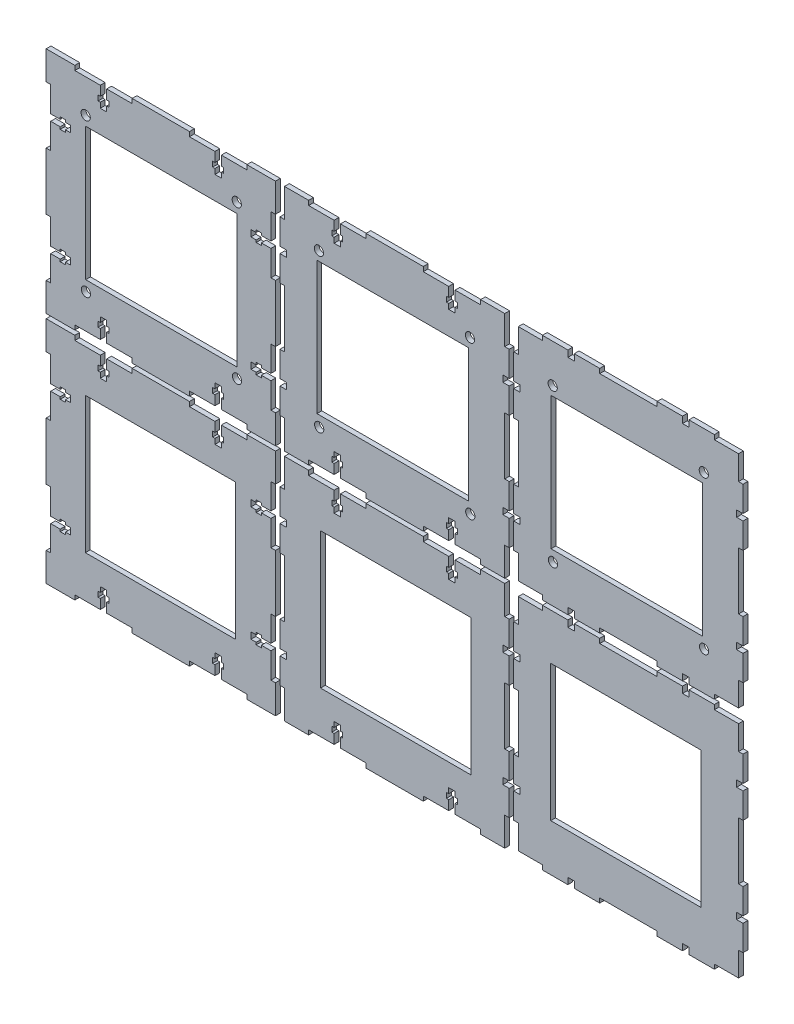
SolidWorks part; units mm, degrees
ref_plane "Front Plane" through (0, 0, 0) normal (0, 0, 1) x (1, 0, 0)
ref_plane "Top Plane" through (0, 0, 0) normal (0, 1, 0) x (1, 0, 0)
ref_plane "Right Plane" through (0, 0, 0) normal (1, 0, 0) x (0, 0, -1)
sketch "Model" plane through (0, 0, 0) normal (0, 0, 1) x (1, 0, 0)
  line L0 (0, 154.3975) -> (0, 135.4704)
  line L1 (0, 135.4704) -> (2.9806, 135.4704)
  line L2 (2.9806, 135.4704) -> (2.9806, 118.6546)
  line L3 (2.9806, 118.6546) -> (9.2897, 118.6546)
  line L4 (9.2897, 118.6546) -> (9.2897, 120.1449)
  line L5 (9.2897, 120.1449) -> (12.7174, 120.1449)
  line L6 (12.7174, 120.1449) -> (12.7174, 118.6546)
  line L7 (12.7174, 118.6546) -> (16.1452, 118.6546)
  line L8 (16.1452, 118.6546) -> (16.1452, 114.432)
  line L9 (16.1452, 114.432) -> (12.7174, 114.432)
  line L10 (12.7174, 114.432) -> (12.7174, 112.9417)
  line L11 (12.7174, 112.9417) -> (9.2897, 112.9417)
  line L12 (9.2897, 112.9417) -> (9.2897, 114.432)
  line L13 (9.2897, 114.432) -> (2.9806, 114.432)
  line L14 (2.9806, 114.432) -> (2.9806, 97.6162)
  line L15 (2.9806, 97.6162) -> (0, 97.6162)
  line L16 (0, 97.6162) -> (0, 59.762)
  line L17 (0, 59.762) -> (2.9806, 59.762)
  line L18 (2.9806, 59.762) -> (2.9806, 42.9462)
  line L19 (2.9806, 42.9462) -> (9.2897, 42.9462)
  line L20 (9.2897, 42.9462) -> (9.2897, 44.4365)
  line L21 (9.2897, 44.4365) -> (12.7174, 44.4365)
  line L22 (12.7174, 44.4365) -> (12.7174, 42.9462)
  line L23 (12.7174, 42.9462) -> (16.1452, 42.9462)
  line L24 (16.1452, 42.9462) -> (16.1452, 38.7236)
  line L25 (16.1452, 38.7236) -> (12.7174, 38.7236)
  line L26 (12.7174, 38.7236) -> (12.7174, 37.2332)
  line L27 (12.7174, 37.2332) -> (9.2897, 37.2332)
  line L28 (9.2897, 37.2332) -> (9.2897, 38.7236)
  line L29 (9.2897, 38.7236) -> (2.9806, 38.7236)
  line L30 (2.9806, 38.7236) -> (2.9806, 21.9078)
  line L31 (2.9806, 21.9078) -> (0, 21.9078)
  line L32 (0, 21.9078) -> (0, 2.9806)
  line L33 (0, 2.9806) -> (18.9271, 2.9806)
  line L34 (18.9271, 2.9806) -> (18.9271, 5.9613)
  line L35 (18.9271, 5.9613) -> (35.7429, 5.9613)
  line L36 (35.7429, 5.9613) -> (35.7429, 12.2703)
  line L37 (35.7429, 12.2703) -> (34.2526, 12.2703)
  line L38 (34.2526, 12.2703) -> (34.2526, 15.6981)
  line L39 (34.2526, 15.6981) -> (35.7429, 15.6981)
  line L40 (35.7429, 15.6981) -> (35.7429, 19.1258)
  line L41 (35.7429, 19.1258) -> (39.9655, 19.1258)
  line L42 (39.9655, 19.1258) -> (39.9655, 15.6981)
  line L43 (39.9655, 15.6981) -> (41.4558, 15.6981)
  line L44 (41.4558, 15.6981) -> (41.4558, 12.2703)
  line L45 (41.4558, 12.2703) -> (39.9655, 12.2703)
  line L46 (39.9655, 12.2703) -> (39.9655, 5.9613)
  line L47 (39.9655, 5.9613) -> (56.7813, 5.9613)
  line L48 (56.7813, 5.9613) -> (56.7813, 2.9806)
  line L49 (56.7813, 2.9806) -> (94.6355, 2.9806)
  line L50 (94.6355, 2.9806) -> (94.6355, 5.9613)
  line L51 (94.6355, 5.9613) -> (111.4513, 5.9613)
  line L52 (111.4513, 5.9613) -> (111.4513, 12.2703)
  line L53 (111.4513, 12.2703) -> (109.961, 12.2703)
  line L54 (109.961, 12.2703) -> (109.961, 15.6981)
  line L55 (109.961, 15.6981) -> (111.4513, 15.6981)
  line L56 (111.4513, 15.6981) -> (111.4513, 19.1258)
  line L57 (111.4513, 19.1258) -> (115.6739, 19.1258)
  line L58 (115.6739, 19.1258) -> (115.6739, 15.6981)
  line L59 (115.6739, 15.6981) -> (117.1643, 15.6981)
  line L60 (117.1643, 15.6981) -> (117.1643, 12.2703)
  line L61 (117.1643, 12.2703) -> (115.6739, 12.2703)
  line L62 (115.6739, 12.2703) -> (115.6739, 5.9613)
  line L63 (115.6739, 5.9613) -> (132.4897, 5.9613)
  line L64 (132.4897, 5.9613) -> (132.4897, 2.9806)
  line L65 (132.4897, 2.9806) -> (151.4169, 2.9806)
  line L66 (151.4169, 2.9806) -> (151.4169, 21.9078)
  line L67 (151.4169, 21.9078) -> (148.4362, 21.9078)
  line L68 (148.4362, 21.9078) -> (148.4362, 38.7236)
  line L69 (148.4362, 38.7236) -> (142.1272, 38.7236)
  line L70 (142.1272, 38.7236) -> (142.1272, 37.2332)
  line L71 (142.1272, 37.2332) -> (138.6994, 37.2332)
  line L72 (138.6994, 37.2332) -> (138.6994, 38.7236)
  line L73 (138.6994, 38.7236) -> (135.2717, 38.7236)
  line L74 (135.2717, 38.7236) -> (135.2717, 42.9462)
  line L75 (135.2717, 42.9462) -> (138.6994, 42.9462)
  line L76 (138.6994, 42.9462) -> (138.6994, 44.4365)
  line L77 (138.6994, 44.4365) -> (142.1272, 44.4365)
  line L78 (142.1272, 44.4365) -> (142.1272, 42.9462)
  line L79 (142.1272, 42.9462) -> (148.4362, 42.9462)
  line L80 (148.4362, 42.9462) -> (148.4362, 59.762)
  line L81 (148.4362, 59.762) -> (151.4169, 59.762)
  line L82 (151.4169, 59.762) -> (151.4169, 97.6162)
  line L83 (151.4169, 97.6162) -> (148.4362, 97.6162)
  line L84 (148.4362, 97.6162) -> (148.4362, 114.432)
  line L85 (148.4362, 114.432) -> (142.1272, 114.432)
  line L86 (142.1272, 114.432) -> (142.1272, 112.9417)
  line L87 (142.1272, 112.9417) -> (138.6994, 112.9417)
  line L88 (138.6994, 112.9417) -> (138.6994, 114.432)
  line L89 (138.6994, 114.432) -> (135.2717, 114.432)
  line L90 (135.2717, 114.432) -> (135.2717, 118.6546)
  line L91 (135.2717, 118.6546) -> (138.6994, 118.6546)
  line L92 (138.6994, 118.6546) -> (138.6994, 120.1449)
  line L93 (138.6994, 120.1449) -> (142.1272, 120.1449)
  line L94 (142.1272, 120.1449) -> (142.1272, 118.6546)
  line L95 (142.1272, 118.6546) -> (148.4362, 118.6546)
  line L96 (148.4362, 118.6546) -> (148.4362, 135.4704)
  line L97 (148.4362, 135.4704) -> (151.4169, 135.4704)
  line L98 (151.4169, 135.4704) -> (151.4169, 154.3975)
  line L99 (151.4169, 154.3975) -> (132.4897, 154.3975)
  line L100 (132.4897, 154.3975) -> (132.4897, 151.4169)
  line L101 (132.4897, 151.4169) -> (115.6739, 151.4169)
  line L102 (115.6739, 151.4169) -> (115.6739, 145.1078)
  line L103 (115.6739, 145.1078) -> (117.1643, 145.1078)
  line L104 (117.1643, 145.1078) -> (117.1643, 141.6801)
  line L105 (117.1643, 141.6801) -> (115.6739, 141.6801)
  line L106 (115.6739, 141.6801) -> (115.6739, 138.2523)
  line L107 (115.6739, 138.2523) -> (111.4513, 138.2523)
  line L108 (111.4513, 138.2523) -> (111.4513, 141.6801)
  line L109 (111.4513, 141.6801) -> (109.961, 141.6801)
  line L110 (109.961, 141.6801) -> (109.961, 145.1078)
  line L111 (109.961, 145.1078) -> (111.4513, 145.1078)
  line L112 (111.4513, 145.1078) -> (111.4513, 151.4169)
  line L113 (111.4513, 151.4169) -> (94.6355, 151.4169)
  line L114 (94.6355, 151.4169) -> (94.6355, 154.3975)
  line L115 (94.6355, 154.3975) -> (56.7813, 154.3975)
  line L116 (56.7813, 154.3975) -> (56.7813, 151.4169)
  line L117 (56.7813, 151.4169) -> (39.9655, 151.4169)
  line L118 (39.9655, 151.4169) -> (39.9655, 145.1078)
  line L119 (39.9655, 145.1078) -> (41.4558, 145.1078)
  line L120 (41.4558, 145.1078) -> (41.4558, 141.6801)
  line L121 (41.4558, 141.6801) -> (39.9655, 141.6801)
  line L122 (39.9655, 141.6801) -> (39.9655, 138.2523)
  line L123 (39.9655, 138.2523) -> (35.7429, 138.2523)
  line L124 (35.7429, 138.2523) -> (35.7429, 141.6801)
  line L125 (35.7429, 141.6801) -> (34.2526, 141.6801)
  line L126 (34.2526, 141.6801) -> (34.2526, 145.1078)
  line L127 (34.2526, 145.1078) -> (35.7429, 145.1078)
  line L128 (35.7429, 145.1078) -> (35.7429, 151.4169)
  line L129 (35.7429, 151.4169) -> (18.9271, 151.4169)
  line L130 (18.9271, 151.4169) -> (18.9271, 154.3975)
  line L131 (18.9271, 154.3975) -> (0, 154.3975)
  line L132 (157.3781, 154.3975) -> (157.3781, 135.4704)
  line L133 (157.3781, 135.4704) -> (154.3975, 135.4704)
  line L134 (154.3975, 135.4704) -> (154.3975, 118.6546)
  line L135 (154.3975, 118.6546) -> (158.6201, 118.6546)
  line L136 (158.6201, 118.6546) -> (158.6201, 116.5433)
  line L137 (158.6201, 116.5433) -> (158.6201, 114.432)
  line L138 (158.6201, 114.432) -> (154.3975, 114.432)
  line L139 (154.3975, 114.432) -> (154.3975, 97.6162)
  line L140 (154.3975, 97.6162) -> (157.3781, 97.6162)
  line L141 (157.3781, 97.6162) -> (157.3781, 59.762)
  line L142 (157.3781, 59.762) -> (154.3975, 59.762)
  line L143 (154.3975, 59.762) -> (154.3975, 42.9462)
  line L144 (154.3975, 42.9462) -> (158.6201, 42.9462)
  line L145 (158.6201, 42.9462) -> (158.6201, 40.8349)
  line L146 (158.6201, 40.8349) -> (158.6201, 38.7236)
  line L147 (158.6201, 38.7236) -> (154.3975, 38.7236)
  line L148 (154.3975, 38.7236) -> (154.3975, 21.9078)
  line L149 (154.3975, 21.9078) -> (157.3781, 21.9078)
  line L150 (157.3781, 21.9078) -> (157.3781, 2.9806)
  line L151 (157.3781, 2.9806) -> (173.3246, 2.9806)
  line L152 (173.3246, 2.9806) -> (173.3246, 5.9613)
  line L153 (173.3246, 5.9613) -> (190.1404, 5.9613)
  line L154 (190.1404, 5.9613) -> (190.1404, 12.2703)
  line L155 (190.1404, 12.2703) -> (188.6501, 12.2703)
  line L156 (188.6501, 12.2703) -> (188.6501, 15.6981)
  line L157 (188.6501, 15.6981) -> (190.1404, 15.6981)
  line L158 (190.1404, 15.6981) -> (190.1404, 19.1258)
  line L159 (190.1404, 19.1258) -> (194.363, 19.1258)
  line L160 (194.363, 19.1258) -> (194.363, 15.6981)
  line L161 (194.363, 15.6981) -> (195.8533, 15.6981)
  line L162 (195.8533, 15.6981) -> (195.8533, 12.2703)
  line L163 (195.8533, 12.2703) -> (194.363, 12.2703)
  line L164 (194.363, 12.2703) -> (194.363, 5.9613)
  line L165 (194.363, 5.9613) -> (211.1788, 5.9613)
  line L166 (211.1788, 5.9613) -> (211.1788, 2.9806)
  line L167 (211.1788, 2.9806) -> (249.033, 2.9806)
  line L168 (249.033, 2.9806) -> (249.033, 5.9613)
  line L169 (249.033, 5.9613) -> (265.8489, 5.9613)
  line L170 (265.8489, 5.9613) -> (265.8489, 12.2703)
  line L171 (265.8489, 12.2703) -> (264.3585, 12.2703)
  line L172 (264.3585, 12.2703) -> (264.3585, 15.6981)
  line L173 (264.3585, 15.6981) -> (265.8489, 15.6981)
  line L174 (265.8489, 15.6981) -> (265.8489, 19.1258)
  line L175 (265.8489, 19.1258) -> (270.0714, 19.1258)
  line L176 (270.0714, 19.1258) -> (270.0714, 15.6981)
  line L177 (270.0714, 15.6981) -> (271.5618, 15.6981)
  line L178 (271.5618, 15.6981) -> (271.5618, 12.2703)
  line L179 (271.5618, 12.2703) -> (270.0714, 12.2703)
  line L180 (270.0714, 12.2703) -> (270.0714, 5.9613)
  line L181 (270.0714, 5.9613) -> (286.8873, 5.9613)
  line L182 (286.8873, 5.9613) -> (286.8873, 2.9806)
  line L183 (286.8873, 2.9806) -> (302.8337, 2.9806)
  line L184 (302.8337, 2.9806) -> (302.8337, 21.9078)
  line L185 (302.8337, 21.9078) -> (305.8144, 21.9078)
  line L186 (305.8144, 21.9078) -> (305.8144, 38.7236)
  line L187 (305.8144, 38.7236) -> (301.5918, 38.7236)
  line L188 (301.5918, 38.7236) -> (301.5918, 40.8349)
  line L189 (301.5918, 40.8349) -> (301.5918, 42.9462)
  line L190 (301.5918, 42.9462) -> (305.8144, 42.9462)
  line L191 (305.8144, 42.9462) -> (305.8144, 59.762)
  line L192 (305.8144, 59.762) -> (302.8337, 59.762)
  line L193 (302.8337, 59.762) -> (302.8337, 97.6162)
  line L194 (302.8337, 97.6162) -> (305.8144, 97.6162)
  line L195 (305.8144, 97.6162) -> (305.8144, 114.432)
  line L196 (305.8144, 114.432) -> (301.5918, 114.432)
  line L197 (301.5918, 114.432) -> (301.5918, 116.5433)
  line L198 (301.5918, 116.5433) -> (301.5918, 118.6546)
  line L199 (301.5918, 118.6546) -> (305.8144, 118.6546)
  line L200 (305.8144, 118.6546) -> (305.8144, 135.4704)
  line L201 (305.8144, 135.4704) -> (302.8337, 135.4704)
  line L202 (302.8337, 135.4704) -> (302.8337, 154.3975)
  line L203 (302.8337, 154.3975) -> (286.8873, 154.3975)
  line L204 (286.8873, 154.3975) -> (286.8873, 151.4169)
  line L205 (286.8873, 151.4169) -> (270.0714, 151.4169)
  line L206 (270.0714, 151.4169) -> (270.0714, 145.1078)
  line L207 (270.0714, 145.1078) -> (271.5618, 145.1078)
  line L208 (271.5618, 145.1078) -> (271.5618, 141.6801)
  line L209 (271.5618, 141.6801) -> (270.0714, 141.6801)
  line L210 (270.0714, 141.6801) -> (270.0714, 138.2523)
  line L211 (270.0714, 138.2523) -> (265.8489, 138.2523)
  line L212 (265.8489, 138.2523) -> (265.8489, 141.6801)
  line L213 (265.8489, 141.6801) -> (264.3585, 141.6801)
  line L214 (264.3585, 141.6801) -> (264.3585, 145.1078)
  line L215 (264.3585, 145.1078) -> (265.8489, 145.1078)
  line L216 (265.8489, 145.1078) -> (265.8489, 151.4169)
  line L217 (265.8489, 151.4169) -> (249.033, 151.4169)
  line L218 (249.033, 151.4169) -> (249.033, 154.3975)
  line L219 (249.033, 154.3975) -> (211.1788, 154.3975)
  line L220 (211.1788, 154.3975) -> (211.1788, 151.4169)
  line L221 (211.1788, 151.4169) -> (194.363, 151.4169)
  line L222 (194.363, 151.4169) -> (194.363, 145.1078)
  line L223 (194.363, 145.1078) -> (195.8533, 145.1078)
  line L224 (195.8533, 145.1078) -> (195.8533, 141.6801)
  line L225 (195.8533, 141.6801) -> (194.363, 141.6801)
  line L226 (194.363, 141.6801) -> (194.363, 138.2523)
  line L227 (194.363, 138.2523) -> (190.1404, 138.2523)
  line L228 (190.1404, 138.2523) -> (190.1404, 141.6801)
  line L229 (190.1404, 141.6801) -> (188.6501, 141.6801)
  line L230 (188.6501, 141.6801) -> (188.6501, 145.1078)
  line L231 (188.6501, 145.1078) -> (190.1404, 145.1078)
  line L232 (190.1404, 145.1078) -> (190.1404, 151.4169)
  line L233 (190.1404, 151.4169) -> (173.3246, 151.4169)
  line L234 (173.3246, 151.4169) -> (173.3246, 154.3975)
  line L235 (173.3246, 154.3975) -> (157.3781, 154.3975)
  line L236 (311.7757, 151.4169) -> (311.7757, 135.4704)
  line L237 (311.7757, 135.4704) -> (308.795, 135.4704)
  line L238 (308.795, 135.4704) -> (308.795, 118.6546)
  line L239 (308.795, 118.6546) -> (313.0176, 118.6546)
  line L240 (313.0176, 118.6546) -> (313.0176, 116.5433)
  line L241 (313.0176, 116.5433) -> (313.0176, 114.432)
  line L242 (313.0176, 114.432) -> (308.795, 114.432)
  line L243 (308.795, 114.432) -> (308.795, 97.6162)
  line L244 (308.795, 97.6162) -> (311.7757, 97.6162)
  line L245 (311.7757, 97.6162) -> (311.7757, 59.762)
  line L246 (311.7757, 59.762) -> (308.795, 59.762)
  line L247 (308.795, 59.762) -> (308.795, 42.9462)
  line L248 (308.795, 42.9462) -> (313.0176, 42.9462)
  line L249 (313.0176, 42.9462) -> (313.0176, 40.8349)
  line L250 (313.0176, 40.8349) -> (313.0176, 38.7236)
  line L251 (313.0176, 38.7236) -> (308.795, 38.7236)
  line L252 (308.795, 38.7236) -> (308.795, 21.9078)
  line L253 (308.795, 21.9078) -> (311.7757, 21.9078)
  line L254 (311.7757, 21.9078) -> (311.7757, 5.9613)
  line L255 (311.7757, 5.9613) -> (327.7221, 5.9613)
  line L256 (327.7221, 5.9613) -> (327.7221, 2.9806)
  line L257 (327.7221, 2.9806) -> (344.5379, 2.9806)
  line L258 (344.5379, 2.9806) -> (344.5379, 7.2032)
  line L259 (344.5379, 7.2032) -> (346.6492, 7.2032)
  line L260 (346.6492, 7.2032) -> (348.7605, 7.2032)
  line L261 (348.7605, 7.2032) -> (348.7605, 2.9806)
  line L262 (348.7605, 2.9806) -> (365.5763, 2.9806)
  line L263 (365.5763, 2.9806) -> (365.5763, 5.9613)
  line L264 (365.5763, 5.9613) -> (403.4305, 5.9613)
  line L265 (403.4305, 5.9613) -> (403.4305, 2.9806)
  line L266 (403.4305, 2.9806) -> (420.2464, 2.9806)
  line L267 (420.2464, 2.9806) -> (420.2464, 7.2032)
  line L268 (420.2464, 7.2032) -> (422.3576, 7.2032)
  line L269 (422.3576, 7.2032) -> (424.4689, 7.2032)
  line L270 (424.4689, 7.2032) -> (424.4689, 2.9806)
  line L271 (424.4689, 2.9806) -> (441.2848, 2.9806)
  line L272 (441.2848, 2.9806) -> (441.2848, 5.9613)
  line L273 (441.2848, 5.9613) -> (457.2312, 5.9613)
  line L274 (457.2312, 5.9613) -> (457.2312, 21.9078)
  line L275 (457.2312, 21.9078) -> (460.2119, 21.9078)
  line L276 (460.2119, 21.9078) -> (460.2119, 38.7236)
  line L277 (460.2119, 38.7236) -> (455.9893, 38.7236)
  line L278 (455.9893, 38.7236) -> (455.9893, 40.8349)
  line L279 (455.9893, 40.8349) -> (455.9893, 42.9462)
  line L280 (455.9893, 42.9462) -> (460.2119, 42.9462)
  line L281 (460.2119, 42.9462) -> (460.2119, 59.762)
  line L282 (460.2119, 59.762) -> (457.2312, 59.762)
  line L283 (457.2312, 59.762) -> (457.2312, 97.6162)
  line L284 (457.2312, 97.6162) -> (460.2119, 97.6162)
  line L285 (460.2119, 97.6162) -> (460.2119, 114.432)
  line L286 (460.2119, 114.432) -> (455.9893, 114.432)
  line L287 (455.9893, 114.432) -> (455.9893, 116.5433)
  line L288 (455.9893, 116.5433) -> (455.9893, 118.6546)
  line L289 (455.9893, 118.6546) -> (460.2119, 118.6546)
  line L290 (460.2119, 118.6546) -> (460.2119, 135.4704)
  line L291 (460.2119, 135.4704) -> (457.2312, 135.4704)
  line L292 (457.2312, 135.4704) -> (457.2312, 151.4169)
  line L293 (457.2312, 151.4169) -> (441.2848, 151.4169)
  line L294 (441.2848, 151.4169) -> (441.2848, 154.3975)
  line L295 (441.2848, 154.3975) -> (424.4689, 154.3975)
  line L296 (424.4689, 154.3975) -> (424.4689, 150.1749)
  line L297 (424.4689, 150.1749) -> (422.3576, 150.1749)
  line L298 (422.3576, 150.1749) -> (420.2464, 150.1749)
  line L299 (420.2464, 150.1749) -> (420.2464, 154.3975)
  line L300 (420.2464, 154.3975) -> (403.4305, 154.3975)
  line L301 (403.4305, 154.3975) -> (403.4305, 151.4169)
  line L302 (403.4305, 151.4169) -> (365.5763, 151.4169)
  line L303 (365.5763, 151.4169) -> (365.5763, 154.3975)
  line L304 (365.5763, 154.3975) -> (348.7605, 154.3975)
  line L305 (348.7605, 154.3975) -> (348.7605, 150.1749)
  line L306 (348.7605, 150.1749) -> (346.6492, 150.1749)
  line L307 (346.6492, 150.1749) -> (344.5379, 150.1749)
  line L308 (344.5379, 150.1749) -> (344.5379, 154.3975)
  line L309 (344.5379, 154.3975) -> (327.7221, 154.3975)
  line L310 (327.7221, 154.3975) -> (327.7221, 151.4169)
  line L311 (327.7221, 151.4169) -> (311.7757, 151.4169)
  line L312 (0, 308.795) -> (0, 289.8679)
  line L313 (0, 289.8679) -> (2.9806, 289.8679)
  line L314 (2.9806, 289.8679) -> (2.9806, 273.0521)
  line L315 (2.9806, 273.0521) -> (9.2897, 273.0521)
  line L316 (9.2897, 273.0521) -> (9.2897, 274.5424)
  line L317 (9.2897, 274.5424) -> (12.7174, 274.5424)
  line L318 (12.7174, 274.5424) -> (12.7174, 273.0521)
  line L319 (12.7174, 273.0521) -> (16.1452, 273.0521)
  line L320 (16.1452, 273.0521) -> (16.1452, 268.8295)
  line L321 (16.1452, 268.8295) -> (12.7174, 268.8295)
  line L322 (12.7174, 268.8295) -> (12.7174, 267.3392)
  line L323 (12.7174, 267.3392) -> (9.2897, 267.3392)
  line L324 (9.2897, 267.3392) -> (9.2897, 268.8295)
  line L325 (9.2897, 268.8295) -> (2.9806, 268.8295)
  line L326 (2.9806, 268.8295) -> (2.9806, 252.0137)
  line L327 (2.9806, 252.0137) -> (0, 252.0137)
  line L328 (0, 252.0137) -> (0, 214.1595)
  line L329 (0, 214.1595) -> (2.9806, 214.1595)
  line L330 (2.9806, 214.1595) -> (2.9806, 197.3437)
  line L331 (2.9806, 197.3437) -> (9.2897, 197.3437)
  line L332 (9.2897, 197.3437) -> (9.2897, 198.834)
  line L333 (9.2897, 198.834) -> (12.7174, 198.834)
  line L334 (12.7174, 198.834) -> (12.7174, 197.3437)
  line L335 (12.7174, 197.3437) -> (16.1452, 197.3437)
  line L336 (16.1452, 197.3437) -> (16.1452, 193.1211)
  line L337 (16.1452, 193.1211) -> (12.7174, 193.1211)
  line L338 (12.7174, 193.1211) -> (12.7174, 191.6307)
  line L339 (12.7174, 191.6307) -> (9.2897, 191.6307)
  line L340 (9.2897, 191.6307) -> (9.2897, 193.1211)
  line L341 (9.2897, 193.1211) -> (2.9806, 193.1211)
  line L342 (2.9806, 193.1211) -> (2.9806, 176.3053)
  line L343 (2.9806, 176.3053) -> (0, 176.3053)
  line L344 (0, 176.3053) -> (0, 157.3781)
  line L345 (0, 157.3781) -> (18.9271, 157.3781)
  line L346 (18.9271, 157.3781) -> (18.9271, 160.3588)
  line L347 (18.9271, 160.3588) -> (35.7429, 160.3588)
  line L348 (35.7429, 160.3588) -> (35.7429, 166.6678)
  line L349 (35.7429, 166.6678) -> (34.2526, 166.6678)
  line L350 (34.2526, 166.6678) -> (34.2526, 170.0956)
  line L351 (34.2526, 170.0956) -> (35.7429, 170.0956)
  line L352 (35.7429, 170.0956) -> (35.7429, 173.5233)
  line L353 (35.7429, 173.5233) -> (39.9655, 173.5233)
  line L354 (39.9655, 173.5233) -> (39.9655, 170.0956)
  line L355 (39.9655, 170.0956) -> (41.4558, 170.0956)
  line L356 (41.4558, 170.0956) -> (41.4558, 166.6678)
  line L357 (41.4558, 166.6678) -> (39.9655, 166.6678)
  line L358 (39.9655, 166.6678) -> (39.9655, 160.3588)
  line L359 (39.9655, 160.3588) -> (56.7813, 160.3588)
  line L360 (56.7813, 160.3588) -> (56.7813, 157.3781)
  line L361 (56.7813, 157.3781) -> (94.6355, 157.3781)
  line L362 (94.6355, 157.3781) -> (94.6355, 160.3588)
  line L363 (94.6355, 160.3588) -> (111.4513, 160.3588)
  line L364 (111.4513, 160.3588) -> (111.4513, 166.6678)
  line L365 (111.4513, 166.6678) -> (109.961, 166.6678)
  line L366 (109.961, 166.6678) -> (109.961, 170.0956)
  line L367 (109.961, 170.0956) -> (111.4513, 170.0956)
  line L368 (111.4513, 170.0956) -> (111.4513, 173.5233)
  line L369 (111.4513, 173.5233) -> (115.6739, 173.5233)
  line L370 (115.6739, 173.5233) -> (115.6739, 170.0956)
  line L371 (115.6739, 170.0956) -> (117.1643, 170.0956)
  line L372 (117.1643, 170.0956) -> (117.1643, 166.6678)
  line L373 (117.1643, 166.6678) -> (115.6739, 166.6678)
  line L374 (115.6739, 166.6678) -> (115.6739, 160.3588)
  line L375 (115.6739, 160.3588) -> (132.4897, 160.3588)
  line L376 (132.4897, 160.3588) -> (132.4897, 157.3781)
  line L377 (132.4897, 157.3781) -> (151.4169, 157.3781)
  line L378 (151.4169, 157.3781) -> (151.4169, 176.3053)
  line L379 (151.4169, 176.3053) -> (148.4362, 176.3053)
  line L380 (148.4362, 176.3053) -> (148.4362, 193.1211)
  line L381 (148.4362, 193.1211) -> (142.1272, 193.1211)
  line L382 (142.1272, 193.1211) -> (142.1272, 191.6307)
  line L383 (142.1272, 191.6307) -> (138.6994, 191.6307)
  line L384 (138.6994, 191.6307) -> (138.6994, 193.1211)
  line L385 (138.6994, 193.1211) -> (135.2717, 193.1211)
  line L386 (135.2717, 193.1211) -> (135.2717, 197.3437)
  line L387 (135.2717, 197.3437) -> (138.6994, 197.3437)
  line L388 (138.6994, 197.3437) -> (138.6994, 198.834)
  line L389 (138.6994, 198.834) -> (142.1272, 198.834)
  line L390 (142.1272, 198.834) -> (142.1272, 197.3437)
  line L391 (142.1272, 197.3437) -> (148.4362, 197.3437)
  line L392 (148.4362, 197.3437) -> (148.4362, 214.1595)
  line L393 (148.4362, 214.1595) -> (151.4169, 214.1595)
  line L394 (151.4169, 214.1595) -> (151.4169, 252.0137)
  line L395 (151.4169, 252.0137) -> (148.4362, 252.0137)
  line L396 (148.4362, 252.0137) -> (148.4362, 268.8295)
  line L397 (148.4362, 268.8295) -> (142.1272, 268.8295)
  line L398 (142.1272, 268.8295) -> (142.1272, 267.3392)
  line L399 (142.1272, 267.3392) -> (138.6994, 267.3392)
  line L400 (138.6994, 267.3392) -> (138.6994, 268.8295)
  line L401 (138.6994, 268.8295) -> (135.2717, 268.8295)
  line L402 (135.2717, 268.8295) -> (135.2717, 273.0521)
  line L403 (135.2717, 273.0521) -> (138.6994, 273.0521)
  line L404 (138.6994, 273.0521) -> (138.6994, 274.5424)
  line L405 (138.6994, 274.5424) -> (142.1272, 274.5424)
  line L406 (142.1272, 274.5424) -> (142.1272, 273.0521)
  line L407 (142.1272, 273.0521) -> (148.4362, 273.0521)
  line L408 (148.4362, 273.0521) -> (148.4362, 289.8679)
  line L409 (148.4362, 289.8679) -> (151.4169, 289.8679)
  line L410 (151.4169, 289.8679) -> (151.4169, 308.795)
  line L411 (151.4169, 308.795) -> (132.4897, 308.795)
  line L412 (132.4897, 308.795) -> (132.4897, 305.8144)
  line L413 (132.4897, 305.8144) -> (115.6739, 305.8144)
  line L414 (115.6739, 305.8144) -> (115.6739, 299.5053)
  line L415 (115.6739, 299.5053) -> (117.1643, 299.5053)
  line L416 (117.1643, 299.5053) -> (117.1643, 296.0776)
  line L417 (117.1643, 296.0776) -> (115.6739, 296.0776)
  line L418 (115.6739, 296.0776) -> (115.6739, 292.6498)
  line L419 (115.6739, 292.6498) -> (111.4513, 292.6498)
  line L420 (111.4513, 292.6498) -> (111.4513, 296.0776)
  line L421 (111.4513, 296.0776) -> (109.961, 296.0776)
  line L422 (109.961, 296.0776) -> (109.961, 299.5053)
  line L423 (109.961, 299.5053) -> (111.4513, 299.5053)
  line L424 (111.4513, 299.5053) -> (111.4513, 305.8144)
  line L425 (111.4513, 305.8144) -> (94.6355, 305.8144)
  line L426 (94.6355, 305.8144) -> (94.6355, 308.795)
  line L427 (94.6355, 308.795) -> (56.7813, 308.795)
  line L428 (56.7813, 308.795) -> (56.7813, 305.8144)
  line L429 (56.7813, 305.8144) -> (39.9655, 305.8144)
  line L430 (39.9655, 305.8144) -> (39.9655, 299.5053)
  line L431 (39.9655, 299.5053) -> (41.4558, 299.5053)
  line L432 (41.4558, 299.5053) -> (41.4558, 296.0776)
  line L433 (41.4558, 296.0776) -> (39.9655, 296.0776)
  line L434 (39.9655, 296.0776) -> (39.9655, 292.6498)
  line L435 (39.9655, 292.6498) -> (35.7429, 292.6498)
  line L436 (35.7429, 292.6498) -> (35.7429, 296.0776)
  line L437 (35.7429, 296.0776) -> (34.2526, 296.0776)
  line L438 (34.2526, 296.0776) -> (34.2526, 299.5053)
  line L439 (34.2526, 299.5053) -> (35.7429, 299.5053)
  line L440 (35.7429, 299.5053) -> (35.7429, 305.8144)
  line L441 (35.7429, 305.8144) -> (18.9271, 305.8144)
  line L442 (18.9271, 305.8144) -> (18.9271, 308.795)
  line L443 (18.9271, 308.795) -> (0, 308.795)
  line L444 (157.3781, 308.795) -> (157.3781, 289.8679)
  line L445 (157.3781, 289.8679) -> (154.3975, 289.8679)
  line L446 (154.3975, 289.8679) -> (154.3975, 273.0521)
  line L447 (154.3975, 273.0521) -> (158.6201, 273.0521)
  line L448 (158.6201, 273.0521) -> (158.6201, 270.9408)
  line L449 (158.6201, 270.9408) -> (158.6201, 268.8295)
  line L450 (158.6201, 268.8295) -> (154.3975, 268.8295)
  line L451 (154.3975, 268.8295) -> (154.3975, 252.0137)
  line L452 (154.3975, 252.0137) -> (157.3781, 252.0137)
  line L453 (157.3781, 252.0137) -> (157.3781, 214.1595)
  line L454 (157.3781, 214.1595) -> (154.3975, 214.1595)
  line L455 (154.3975, 214.1595) -> (154.3975, 197.3437)
  line L456 (154.3975, 197.3437) -> (158.6201, 197.3437)
  line L457 (158.6201, 197.3437) -> (158.6201, 195.2324)
  line L458 (158.6201, 195.2324) -> (158.6201, 193.1211)
  line L459 (158.6201, 193.1211) -> (154.3975, 193.1211)
  line L460 (154.3975, 193.1211) -> (154.3975, 176.3053)
  line L461 (154.3975, 176.3053) -> (157.3781, 176.3053)
  line L462 (157.3781, 176.3053) -> (157.3781, 157.3781)
  line L463 (157.3781, 157.3781) -> (173.3246, 157.3781)
  line L464 (173.3246, 157.3781) -> (173.3246, 160.3588)
  line L465 (173.3246, 160.3588) -> (190.1404, 160.3588)
  line L466 (190.1404, 160.3588) -> (190.1404, 166.6678)
  line L467 (190.1404, 166.6678) -> (188.6501, 166.6678)
  line L468 (188.6501, 166.6678) -> (188.6501, 170.0956)
  line L469 (188.6501, 170.0956) -> (190.1404, 170.0956)
  line L470 (190.1404, 170.0956) -> (190.1404, 173.5233)
  line L471 (190.1404, 173.5233) -> (194.363, 173.5233)
  line L472 (194.363, 173.5233) -> (194.363, 170.0956)
  line L473 (194.363, 170.0956) -> (195.8533, 170.0956)
  line L474 (195.8533, 170.0956) -> (195.8533, 166.6678)
  line L475 (195.8533, 166.6678) -> (194.363, 166.6678)
  line L476 (194.363, 166.6678) -> (194.363, 160.3588)
  line L477 (194.363, 160.3588) -> (211.1788, 160.3588)
  line L478 (211.1788, 160.3588) -> (211.1788, 157.3781)
  line L479 (211.1788, 157.3781) -> (249.033, 157.3781)
  line L480 (249.033, 157.3781) -> (249.033, 160.3588)
  line L481 (249.033, 160.3588) -> (265.8489, 160.3588)
  line L482 (265.8489, 160.3588) -> (265.8489, 166.6678)
  line L483 (265.8489, 166.6678) -> (264.3585, 166.6678)
  line L484 (264.3585, 166.6678) -> (264.3585, 170.0956)
  line L485 (264.3585, 170.0956) -> (265.8489, 170.0956)
  line L486 (265.8489, 170.0956) -> (265.8489, 173.5233)
  line L487 (265.8489, 173.5233) -> (270.0714, 173.5233)
  line L488 (270.0714, 173.5233) -> (270.0714, 170.0956)
  line L489 (270.0714, 170.0956) -> (271.5618, 170.0956)
  line L490 (271.5618, 170.0956) -> (271.5618, 166.6678)
  line L491 (271.5618, 166.6678) -> (270.0714, 166.6678)
  line L492 (270.0714, 166.6678) -> (270.0714, 160.3588)
  line L493 (270.0714, 160.3588) -> (286.8873, 160.3588)
  line L494 (286.8873, 160.3588) -> (286.8873, 157.3781)
  line L495 (286.8873, 157.3781) -> (302.8337, 157.3781)
  line L496 (302.8337, 157.3781) -> (302.8337, 176.3053)
  line L497 (302.8337, 176.3053) -> (305.8144, 176.3053)
  line L498 (305.8144, 176.3053) -> (305.8144, 193.1211)
  line L499 (305.8144, 193.1211) -> (301.5918, 193.1211)
  line L500 (301.5918, 193.1211) -> (301.5918, 195.2324)
  line L501 (301.5918, 195.2324) -> (301.5918, 197.3437)
  line L502 (301.5918, 197.3437) -> (305.8144, 197.3437)
  line L503 (305.8144, 197.3437) -> (305.8144, 214.1595)
  line L504 (305.8144, 214.1595) -> (302.8337, 214.1595)
  line L505 (302.8337, 214.1595) -> (302.8337, 252.0137)
  line L506 (302.8337, 252.0137) -> (305.8144, 252.0137)
  line L507 (305.8144, 252.0137) -> (305.8144, 268.8295)
  line L508 (305.8144, 268.8295) -> (301.5918, 268.8295)
  line L509 (301.5918, 268.8295) -> (301.5918, 270.9408)
  line L510 (301.5918, 270.9408) -> (301.5918, 273.0521)
  line L511 (301.5918, 273.0521) -> (305.8144, 273.0521)
  line L512 (305.8144, 273.0521) -> (305.8144, 289.8679)
  line L513 (305.8144, 289.8679) -> (302.8337, 289.8679)
  line L514 (302.8337, 289.8679) -> (302.8337, 308.795)
  line L515 (302.8337, 308.795) -> (286.8873, 308.795)
  line L516 (286.8873, 308.795) -> (286.8873, 305.8144)
  line L517 (286.8873, 305.8144) -> (270.0714, 305.8144)
  line L518 (270.0714, 305.8144) -> (270.0714, 299.5053)
  line L519 (270.0714, 299.5053) -> (271.5618, 299.5053)
  line L520 (271.5618, 299.5053) -> (271.5618, 296.0776)
  line L521 (271.5618, 296.0776) -> (270.0714, 296.0776)
  line L522 (270.0714, 296.0776) -> (270.0714, 292.6498)
  line L523 (270.0714, 292.6498) -> (265.8489, 292.6498)
  line L524 (265.8489, 292.6498) -> (265.8489, 296.0776)
  line L525 (265.8489, 296.0776) -> (264.3585, 296.0776)
  line L526 (264.3585, 296.0776) -> (264.3585, 299.5053)
  line L527 (264.3585, 299.5053) -> (265.8489, 299.5053)
  line L528 (265.8489, 299.5053) -> (265.8489, 305.8144)
  line L529 (265.8489, 305.8144) -> (249.033, 305.8144)
  line L530 (249.033, 305.8144) -> (249.033, 308.795)
  line L531 (249.033, 308.795) -> (211.1788, 308.795)
  line L532 (211.1788, 308.795) -> (211.1788, 305.8144)
  line L533 (211.1788, 305.8144) -> (194.363, 305.8144)
  line L534 (194.363, 305.8144) -> (194.363, 299.5053)
  line L535 (194.363, 299.5053) -> (195.8533, 299.5053)
  line L536 (195.8533, 299.5053) -> (195.8533, 296.0776)
  line L537 (195.8533, 296.0776) -> (194.363, 296.0776)
  line L538 (194.363, 296.0776) -> (194.363, 292.6498)
  line L539 (194.363, 292.6498) -> (190.1404, 292.6498)
  line L540 (190.1404, 292.6498) -> (190.1404, 296.0776)
  line L541 (190.1404, 296.0776) -> (188.6501, 296.0776)
  line L542 (188.6501, 296.0776) -> (188.6501, 299.5053)
  line L543 (188.6501, 299.5053) -> (190.1404, 299.5053)
  line L544 (190.1404, 299.5053) -> (190.1404, 305.8144)
  line L545 (190.1404, 305.8144) -> (173.3246, 305.8144)
  line L546 (173.3246, 305.8144) -> (173.3246, 308.795)
  line L547 (173.3246, 308.795) -> (157.3781, 308.795)
  line L548 (311.7757, 305.8144) -> (311.7757, 289.8679)
  line L549 (311.7757, 289.8679) -> (308.795, 289.8679)
  line L550 (308.795, 289.8679) -> (308.795, 273.0521)
  line L551 (308.795, 273.0521) -> (313.0176, 273.0521)
  line L552 (313.0176, 273.0521) -> (313.0176, 270.9408)
  line L553 (313.0176, 270.9408) -> (313.0176, 268.8295)
  line L554 (313.0176, 268.8295) -> (308.795, 268.8295)
  line L555 (308.795, 268.8295) -> (308.795, 252.0137)
  line L556 (308.795, 252.0137) -> (311.7757, 252.0137)
  line L557 (311.7757, 252.0137) -> (311.7757, 214.1595)
  line L558 (311.7757, 214.1595) -> (308.795, 214.1595)
  line L559 (308.795, 214.1595) -> (308.795, 197.3437)
  line L560 (308.795, 197.3437) -> (313.0176, 197.3437)
  line L561 (313.0176, 197.3437) -> (313.0176, 195.2324)
  line L562 (313.0176, 195.2324) -> (313.0176, 193.1211)
  line L563 (313.0176, 193.1211) -> (308.795, 193.1211)
  line L564 (308.795, 193.1211) -> (308.795, 176.3053)
  line L565 (308.795, 176.3053) -> (311.7757, 176.3053)
  line L566 (311.7757, 176.3053) -> (311.7757, 160.3588)
  line L567 (311.7757, 160.3588) -> (327.7221, 160.3588)
  line L568 (327.7221, 160.3588) -> (327.7221, 157.3781)
  line L569 (327.7221, 157.3781) -> (344.5379, 157.3781)
  line L570 (344.5379, 157.3781) -> (344.5379, 161.6007)
  line L571 (344.5379, 161.6007) -> (346.6492, 161.6007)
  line L572 (346.6492, 161.6007) -> (348.7605, 161.6007)
  line L573 (348.7605, 161.6007) -> (348.7605, 157.3781)
  line L574 (348.7605, 157.3781) -> (365.5763, 157.3781)
  line L575 (365.5763, 157.3781) -> (365.5763, 160.3588)
  line L576 (365.5763, 160.3588) -> (403.4305, 160.3588)
  line L577 (403.4305, 160.3588) -> (403.4305, 157.3781)
  line L578 (403.4305, 157.3781) -> (420.2464, 157.3781)
  line L579 (420.2464, 157.3781) -> (420.2464, 161.6007)
  line L580 (420.2464, 161.6007) -> (422.3576, 161.6007)
  line L581 (422.3576, 161.6007) -> (424.4689, 161.6007)
  line L582 (424.4689, 161.6007) -> (424.4689, 157.3781)
  line L583 (424.4689, 157.3781) -> (441.2848, 157.3781)
  line L584 (441.2848, 157.3781) -> (441.2848, 160.3588)
  line L585 (441.2848, 160.3588) -> (457.2312, 160.3588)
  line L586 (457.2312, 160.3588) -> (457.2312, 176.3053)
  line L587 (457.2312, 176.3053) -> (460.2119, 176.3053)
  line L588 (460.2119, 176.3053) -> (460.2119, 193.1211)
  line L589 (460.2119, 193.1211) -> (455.9893, 193.1211)
  line L590 (455.9893, 193.1211) -> (455.9893, 195.2324)
  line L591 (455.9893, 195.2324) -> (455.9893, 197.3437)
  line L592 (455.9893, 197.3437) -> (460.2119, 197.3437)
  line L593 (460.2119, 197.3437) -> (460.2119, 214.1595)
  line L594 (460.2119, 214.1595) -> (457.2312, 214.1595)
  line L595 (457.2312, 214.1595) -> (457.2312, 252.0137)
  line L596 (457.2312, 252.0137) -> (460.2119, 252.0137)
  line L597 (460.2119, 252.0137) -> (460.2119, 268.8295)
  line L598 (460.2119, 268.8295) -> (455.9893, 268.8295)
  line L599 (455.9893, 268.8295) -> (455.9893, 270.9408)
  line L600 (455.9893, 270.9408) -> (455.9893, 273.0521)
  line L601 (455.9893, 273.0521) -> (460.2119, 273.0521)
  line L602 (460.2119, 273.0521) -> (460.2119, 289.8679)
  line L603 (460.2119, 289.8679) -> (457.2312, 289.8679)
  line L604 (457.2312, 289.8679) -> (457.2312, 305.8144)
  line L605 (457.2312, 305.8144) -> (441.2848, 305.8144)
  line L606 (441.2848, 305.8144) -> (441.2848, 308.795)
  line L607 (441.2848, 308.795) -> (424.4689, 308.795)
  line L608 (424.4689, 308.795) -> (424.4689, 304.5724)
  line L609 (424.4689, 304.5724) -> (422.3576, 304.5724)
  line L610 (422.3576, 304.5724) -> (420.2464, 304.5724)
  line L611 (420.2464, 304.5724) -> (420.2464, 308.795)
  line L612 (420.2464, 308.795) -> (403.4305, 308.795)
  line L613 (403.4305, 308.795) -> (403.4305, 305.8144)
  line L614 (403.4305, 305.8144) -> (365.5763, 305.8144)
  line L615 (365.5763, 305.8144) -> (365.5763, 308.795)
  line L616 (365.5763, 308.795) -> (348.7605, 308.795)
  line L617 (348.7605, 308.795) -> (348.7605, 304.5724)
  line L618 (348.7605, 304.5724) -> (346.6492, 304.5724)
  line L619 (346.6492, 304.5724) -> (344.5379, 304.5724)
  line L620 (344.5379, 304.5724) -> (344.5379, 308.795)
  line L621 (344.5379, 308.795) -> (327.7221, 308.795)
  line L622 (327.7221, 308.795) -> (327.7221, 305.8144)
  line L623 (327.7221, 305.8144) -> (311.7757, 305.8144)
  line L624 (75.7084, 308.795) -> (75.7084, 157.3781) construction
  line L625 (0, 233.0866) -> (151.4169, 233.0866) construction
  line L626 (157.3781, 233.0866) -> (302.8337, 233.0866) construction
  line L627 (311.7757, 233.0866) -> (457.2312, 233.0866) construction
  line L628 (0, 78.6891) -> (151.4169, 78.6891) construction
  line L629 (157.3781, 78.6891) -> (302.8337, 78.6891) construction
  line L630 (311.7757, 78.6891) -> (457.2312, 78.6891) construction
  line L631 (230.1059, 308.795) -> (230.1059, 157.3781) construction
  line L632 (384.5034, 305.8144) -> (384.5034, 160.3588) construction
  line L633 (75.7084, 154.3975) -> (75.7084, 2.9806) construction
  line L634 (230.1059, 154.3975) -> (230.1059, 2.9806) construction
  line L635 (384.5034, 151.4169) -> (384.5034, 5.9613) construction
  line L648 (25.8702, 123.5522) -> (125.1984, 123.5522)
  line L649 (25.8702, 123.5522) -> (25.8702, 33.5522)
  line L650 (25.8702, 33.5522) -> (125.1984, 33.5522)
  line L651 (125.1984, 123.5522) -> (125.1984, 33.5522)
  line L652 (181.1929, 123.7615) -> (280.5211, 123.7615)
  line L653 (181.1929, 123.7615) -> (181.1929, 33.7615)
  line L654 (181.1929, 33.7615) -> (280.5211, 33.7615)
  line L655 (280.5211, 123.7615) -> (280.5211, 33.7615)
  line L656 (333.225, 123.9331) -> (432.5532, 123.9331)
  line L657 (333.225, 123.9331) -> (333.225, 33.9331)
  line L658 (333.225, 33.9331) -> (432.5532, 33.9331)
  line L659 (432.5532, 123.9331) -> (432.5532, 33.9331)
  line L660 (178.8227, 277.2912) -> (278.7958, 277.2912)
  line L661 (26.0877, 277.5284) -> (126.0608, 277.5284)
  line L662 (26.0877, 277.5284) -> (26.0877, 189.7833)
  line L663 (26.0877, 189.7833) -> (126.0608, 189.7833)
  line L664 (126.0608, 277.5284) -> (126.0608, 189.7833)
  line L665 (178.8227, 277.2912) -> (178.8227, 189.5462)
  line L666 (178.8227, 189.5462) -> (278.7958, 189.5462)
  line L667 (278.7958, 277.2912) -> (278.7958, 189.5462)
  line L668 (333.4438, 277.2912) -> (433.4169, 277.2912)
  line L669 (333.4438, 277.2912) -> (333.4438, 189.5462)
  line L670 (333.4438, 189.5462) -> (433.4169, 189.5462)
  line L671 (433.4169, 277.2912) -> (433.4169, 189.5462)
  circle A12 centre (26.0877, 283.8269) radius 3.05
  circle A13 centre (125.8732, 284.0707) radius 3.05
  circle A14 centre (126.0608, 183.1807) radius 3.05
  circle A15 centre (26.2754, 182.9332) radius 3.05
  circle A16 centre (180.1194, 283.4116) radius 3.05
  circle A17 centre (279.9049, 283.6553) radius 3.05
  circle A18 centre (280.0925, 182.7653) radius 3.05
  circle A19 centre (180.3072, 182.5178) radius 3.05
  circle A20 centre (334.5169, 283.4116) radius 3.05
  circle A21 centre (434.3024, 283.6553) radius 3.05
  circle A22 centre (434.49, 182.7653) radius 3.05
  circle A23 centre (334.7047, 182.5178) radius 3.05
  point P648 (75.7084, 233.0866)
  point P675 (75.7084, 78.6891)
  point P684 (230.1059, 78.6891)
  point P693 (384.5034, 78.6891)
extrude "Boss-Extrude1" add sketch "Model" along normal blind 3.175
